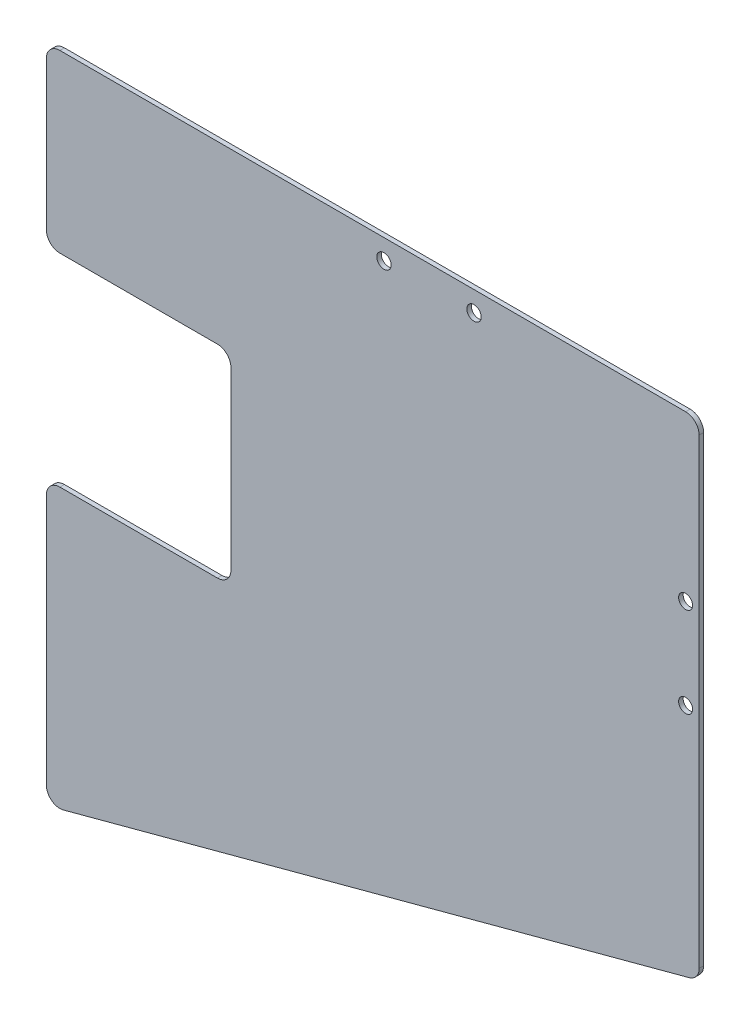
SolidWorks part; units mm, degrees
material "Thornel Mat VMA"
ref_plane "前视基准面" through (0, 0, 0) normal (0, 0, 1) x (1, 0, 0)
ref_plane "上视基准面" through (0, 0, 0) normal (0, 1, 0) x (1, 0, 0)
ref_plane "右视基准面" through (0, 0, 0) normal (1, 0, 0) x (0, 0, -1)
sketch "草图1" plane through (0, 0, 0) normal (0, 0, 1) x (1, 0, 0)
  line L1 (-72.5, -76) -> (72.5, -76)
  line L2 (-72.5, -76) -> (-72.5, 76)
  line L3 (-72.5, 76) -> (72.5, 76)
  line L4 (72.5, -76) -> (72.5, 76)
  line L5 (-72.5, -76) -> (72.5, 76) construction
  line L6 (-72.5, 76) -> (72.5, -76) construction
  point P0 (0, 0)
  dimension "D1" = 152
  dimension "D2" = 145
extrude "凸台-拉伸1" add sketch "草图1" along normal blind 1
sketch "草图2" plane through (0, 0, 0) normal (0, 0, -1) x (-1, 0, 0)
  line L0 (0, 0) -> (-82.7192, 0) construction
  line L1 (-72.5, -35) -> (72.5, -73.8526) construction
  line L3 (31.5, 37) -> (31.5, -8)
  line L4 (-72.5, -76) -> (-72.5, 76) construction
  line L5 (72.5, 76) -> (72.5, -76) construction
  line L6 (31.5, -8) -> (72.5, -8)
  line L7 (72.5, -8) -> (72.5, 37)
  line L8 (72.5, 37) -> (31.5, 37)
  line L10 (-72.5, -31.8942) -> (72.5, -70.7468)
  line L11 (-71.7235, -32.1022) -> (73.2765, -70.9549) construction
  line L12 (-72.5, -31.8942) -> (-72.5, -76)
  line L13 (-72.5, -76) -> (72.5, -76)
  line L14 (72.5, -76) -> (72.5, -70.7468)
  line L15 (-72.5, 76) -> (72.5, 76) construction
  dimension "D1" = 35
  dimension "D2" = 15
  dimension "D4" = 31.5
  dimension "D5" = 45
  dimension "D6" = 39
  dimension "D3" = 3
extrude "切除-拉伸1" cut sketch "草图2" against normal blind 1
sketch "草图3" plane through (0, 0, 1) normal (0, 0, 1) x (1, 0, 0)
  line L0 (0, 0) -> (0, 71.5) construction
  line L1 (0, 71.5) -> (2.5, 71.5) construction
  line L2 (2.5, 71.5) -> (22.5, 71.5) construction
  circle A2 centre (2.5, 71.5) radius 1.6
  circle A3 centre (22.5, 71.5) radius 1.6
  dimension "D4" = 3.2
  dimension "D1" = 71.5
  dimension "D2" = 2.5
  dimension "D3" = 20
extrude "切除-拉伸2" cut sketch "草图3" against normal blind 1
sketch "草图5" [suppressed] plane through (0, 0, 1) normal (0, 0, 1) x (1, 0, 0)
  circle A0 centre (56.3, -25.0228) radius 2 construction
  circle A1 centre (56.3, -9.0228) radius 2 construction
  circle A2 centre (56.3, -25.0228) radius 2
  circle A3 centre (56.3, -9.0228) radius 2
extrude "切除-拉伸4" [suppressed] cut sketch "草图5" against normal blind 10
sketch "草图6" [suppressed] plane through (0, 0, 0) normal (0, 0, -1) x (-1, 0, 0)
  line L1 (-61.9, -17.0228) -> (0, -17.0228) construction
  line L2 (0, -17.0228) -> (0, 0) construction
  line L3 (-63, -30.5228) -> (-60.8, -30.5228)
  line L4 (-63, -30.5228) -> (-63, -3.5228)
  line L5 (-63, -3.5228) -> (-60.8, -3.5228)
  line L6 (-60.8, -30.5228) -> (-60.8, -3.5228)
  line L7 (-63, -30.5228) -> (-60.8, -3.5228) construction
  line L8 (-63, -3.5228) -> (-60.8, -30.5228) construction
  line L9 (-62.5, -35.2889) -> (-62.5, 74.5) construction
  point P2 (-61.9, -17.0228)
  dimension "D1" = 17.0228
  dimension "D2" = 61.9
  dimension "D3" = 27
  dimension "D4" = 1.7
extrude "切除-拉伸5" [suppressed] cut sketch "草图6" against normal blind 10.6
fillet "圆角1" radius 3 8 edges at (-31.5, -8, 0.5) (-31.5, 37, 0.5) (-72.5, 37, 0.5) (-72.5, 76, 0.5) (72.5, 76, 0.5) (72.5, -31.8942, 0.5) (-72.5, -8, 0.5) (-72.5, -70.7468, 0.5)
fillet "圆角2" [suppressed] radius 0.8
fillet "圆角3" [suppressed] radius 3
sketch "草图7" plane through (0, 0, 0) normal (0, 0, -1) x (-1, 0, 0)
  line L0 (0, 0) -> (-69.5, 0) construction
  line L1 (-69.5, 0) -> (-69.5, 19.5) construction
  line L2 (-69.5, 19.5) -> (-69.5, 39.5) construction
  line L3 (-72.5, -29.5922) -> (-72.5, 73) construction
  circle A2 centre (-69.5, 39.5) radius 1.55
  circle A3 centre (-69.5, 19.5) radius 1.55
  dimension "D4" = 3.1
  dimension "D1" = 3
  dimension "D2" = 19.5
  dimension "D3" = 20
extrude "切除-拉伸6" cut sketch "草图7" against normal blind 10
sketch "草图8" [suppressed] plane through (0, 0, 0) normal (0, 0, -1) x (-1, 0, 0)
  line L0 (31.5, 38.5) -> (31.5, -0.5) construction
  line L1 (31.5, 38.5) -> (62.5, 38.5)
  line L2 (31.5, 38.5) -> (31.5, 74.5)
  line L3 (31.5, 74.5) -> (62.5, 74.5)
  line L4 (62.5, 38.5) -> (62.5, 74.5)
  line L5 (-59.5, 74.5) -> (59.5, 74.5) construction
  line L6 (62.5, 71.5) -> (62.5, 44.5) construction
  arc A0 (34.5, 41.5) -> (31.5, 38.5) centre (34.5, 38.5) ccw construction
extrude "切除-拉伸7" [suppressed] cut sketch "草图8" against normal blind 10
fillet "圆角4" [suppressed] radius 3
sketch "草图9" [suppressed] plane through (0, 0, 0) normal (0, 0, -1) x (-1, 0, 0)
  line L8 (-0.5406, 24.61) -> (-0.5406, 32.61)
  line L9 (-2.1406, 32.61) -> (-2.1406, 24.61)
  line L10 (-10.1906, 24.61) -> (-10.1906, 32.61)
  line L11 (-11.7906, 32.61) -> (-11.7906, 24.61)
  line L12 (-19.8406, 24.61) -> (-19.8406, 32.61)
  line L13 (-21.4406, 32.61) -> (-21.4406, 24.61)
  line L14 (-29.49, 24.61) -> (-29.4898, 32.6113)
  line L15 (-31.0887, 32.6087) -> (-31.0891, 24.6087)
  arc A6 (-2.1406, 24.61) -> (-0.5406, 24.61) centre (-1.3406, 24.61) ccw
  arc A7 (-0.5406, 32.61) -> (-2.1406, 32.61) centre (-1.3406, 32.61) ccw
  arc A8 (-10.1906, 32.61) -> (-11.7906, 32.61) centre (-10.9906, 32.61) ccw
  arc A9 (-11.7906, 24.61) -> (-10.1906, 24.61) centre (-10.9906, 24.61) ccw
  arc A10 (-19.8406, 32.61) -> (-21.4406, 32.61) centre (-20.6406, 32.61) ccw
  arc A11 (-21.4406, 24.61) -> (-19.8406, 24.61) centre (-20.6406, 24.61) ccw
  circle A13 centre (-50.67, 28.6) radius 7
  spline S2 degree 3 poles (-29.4898, 32.6113) (-29.49, 32.8203) (-29.5762, 33.0281) (-29.8723, 33.3236) (-30.0803, 33.4096) (-30.4989, 33.4093) (-30.7069, 33.3229) (-31.0028, 33.0265) (-31.0889, 32.8182) (-31.0887, 32.6087) knots 0 0 0 0 0.25 0.25 0.5 0.5 0.75 0.75 1 1 1 1
  spline S3 degree 3 poles (-31.0891, 24.6087) (-31.0889, 24.3998) (-31.0028, 24.1921) (-30.707, 23.8965) (-30.4991, 23.8105) (-30.0807, 23.8105) (-29.8727, 23.8965) (-29.5765, 24.1925) (-29.4902, 24.4005) (-29.49, 24.61) knots 0 0 0 0 0.25 0.25 0.5 0.5 0.75 0.75 1 1 1 1
  dimension "D3" = 14
  dimension "D1" = 28.6
  dimension "D2" = 50.67
extrude "切除-拉伸8" [suppressed] cut sketch "草图9" against normal blind 10
sketch "草图10" [suppressed] plane through (0, 0, 0) normal (0, 0, -1) x (-1, 0, 0)
  line L8 (-73.3076, 9.6607) -> (15.7075, 9.6607) construction
  line L9 (16.9893, 10.9424) -> (16.9893, 46.2575) construction
  line L10 (15.7076, 47.5393) -> (-73.3075, 47.5393) construction
  line L11 (-74.5893, 46.2576) -> (-74.5893, 10.9425) construction
  line L56 (-43.67, 51.5393) -> (-62.5, 51.5393)
  line L57 (-62.5, 5.6607) -> (-43.67, 5.6607)
  line L58 (15.7076, 51.5393) -> (-73.3075, 51.5393) construction
  line L60 (-73.3076, 5.6607) -> (15.7075, 5.6607) construction
  line L61 (-43.67, 51.5393) -> (-43.67, 5.6607)
  line L62 (-62.5, 51.5393) -> (-62.5, 5.6607)
  spline S8 degree 2 poles (15.7075, 9.6607) (15.9609, 9.6598) (16.197, 9.7563) (16.4342, 9.8532) (16.616, 10.035) (16.797, 10.216) (16.8944, 10.4549) (16.9903, 10.69) (16.9893, 10.9424) knots 0 0 0 0.25 0.25 0.5 0.5 0.75 0.75 1 1 1 construction
  spline S9 degree 2 poles (16.9893, 46.2575) (16.9902, 46.5109) (16.8937, 46.747) (16.7968, 46.9842) (16.615, 47.166) (16.434, 47.347) (16.1951, 47.4444) (15.96, 47.5403) (15.7076, 47.5393) knots 0 0 0 0.25 0.25 0.5 0.5 0.75 0.75 1 1 1 construction
  spline S10 degree 2 poles (-73.3075, 47.5393) (-73.5609, 47.5402) (-73.797, 47.4437) (-74.0342, 47.3468) (-74.216, 47.165) (-74.397, 46.984) (-74.4944, 46.7451) (-74.5903, 46.51) (-74.5893, 46.2576) knots 0 0 0 0.25 0.25 0.5 0.5 0.75 0.75 1 1 1 construction
  spline S11 degree 2 poles (-74.5893, 10.9425) (-74.5902, 10.6891) (-74.4937, 10.453) (-74.3968, 10.2158) (-74.215, 10.034) (-74.034, 9.853) (-73.7951, 9.7556) (-73.56, 9.6597) (-73.3076, 9.6607) knots 0 0 0 0.25 0.25 0.5 0.5 0.75 0.75 1 1 1 construction
  dimension "D3" = 18.83
  dimension "D2" = 4
extrude "切除-拉伸9" [suppressed] cut sketch "草图10" against normal blind 10
fillet "圆角5" [suppressed] radius 2
sketch "草图11" [suppressed] plane through (0, 0, 0) normal (0, 0, -1) x (-1, 0, 0)
  line L1 (-43.67, 5.6607) -> (-43.67, 51.5393) construction
  ellipse E0 centre (-43.67, 28.6) end of major axis (-43.67, 16.6) minor radius 10
  dimension "D1" = 20
  dimension "D2" = 24
extrude "切除-拉伸11" [suppressed] cut sketch "草图11" against normal blind 10
fillet "圆角6" [suppressed] radius 2
sketch "草图12" [suppressed] plane through (0, 0, 0) normal (0, 0, -1) x (-1, 0, 0)
  line L0 (56.5, -3.5) -> (56.5, -67.1749)
  line L1 (34.5, -3.5) -> (62.5, -3.5) construction
  line L2 (62.5, -68.7826) -> (-60.2765, -35.8847) construction
  line L3 (62.5, -3.5) -> (62.5, -68.7826) construction
  line L4 (56.5, -3.5) -> (62.5, -3.5)
  line L5 (62.5, -3.5) -> (62.5, -68.7826)
  line L6 (62.5, -68.7826) -> (56.5, -67.1749)
  dimension "D1" = 6
extrude "切除-拉伸12" [suppressed] cut sketch "草图12" against normal blind 10
fillet "圆角7" [suppressed] radius 3
sketch "草图13" [suppressed] plane through (0, 0, 1) normal (0, 0, 1) x (1, 0, 0)
  circle A0 centre (-6, -28.6) radius 1.7 construction
  circle A1 centre (8, -28.6) radius 1.7 construction
  circle A2 centre (-6, -28.6) radius 1.7 construction
  circle A3 centre (8, -28.6) radius 1.7 construction
  circle A4 centre (-6, -28.6) radius 1.6
  circle A5 centre (8, -28.6) radius 1.6
  dimension "D1" = 3.2
extrude "切除-拉伸13" [suppressed] cut sketch "草图13" against normal blind 5
sketch "草图14" [suppressed] plane through (0, 0, 0) normal (0, 0, -1) x (-1, 0, 0)
  circle A0 centre (-57.5, 66.25) radius 1.25 construction
  circle A1 centre (-57.5, 66.25) radius 1.25 construction
  circle A2 centre (-57.5, 66.25) radius 1.6
  dimension "D1" = 3.2
extrude "切除-拉伸14" [suppressed] cut sketch "草图14" against normal blind 10
